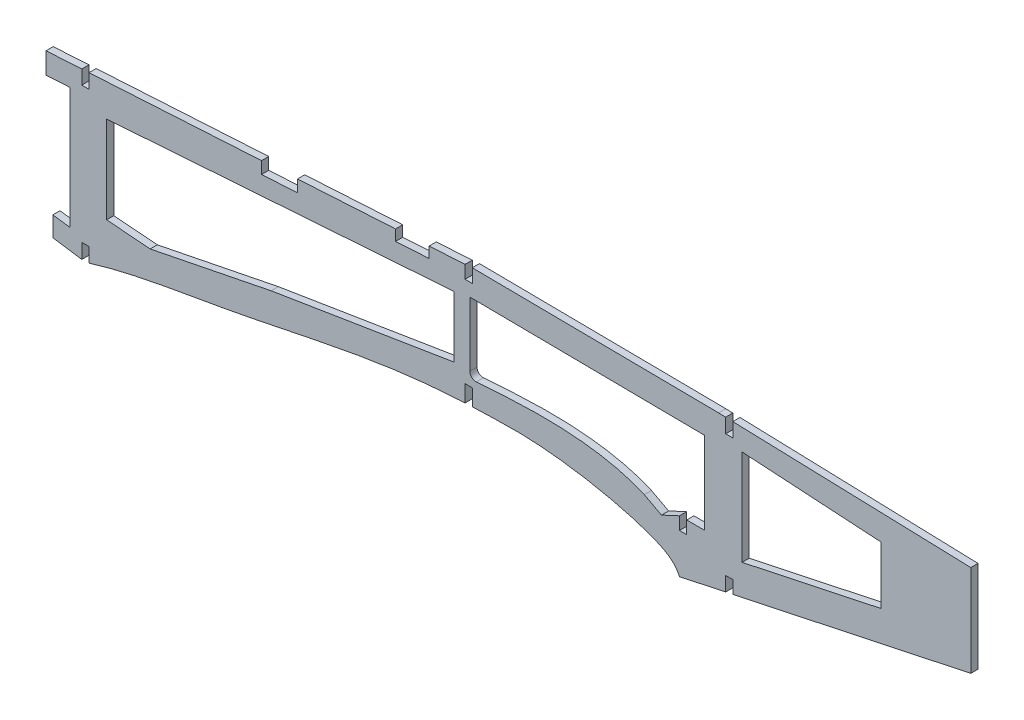
SolidWorks part; units mm, degrees
ref_plane "Front Plane" through (0, 0, 0) normal (0, 0, 1) x (1, 0, 0)
ref_plane "Top Plane" through (0, 0, 0) normal (0, 1, 0) x (1, 0, 0)
ref_plane "Right Plane" through (0, 0, 0) normal (1, 0, 0) x (0, 0, -1)
sketch "Sketch1" plane through (0, 0, 0) normal (0, 0, 1) x (1, 0, 0)
  line L0 (0, 0) -> (110, 0) construction
  line L1 (110, 0) -> (110, 21) construction
  line L2 (0, 0) -> (110, 21)
  line L3 (23.5, 17.3139) -> (20, 16.6457)
  line L4 (0, 0) -> (20, 0)
  line L5 (20, 0) -> (20, 67.15) construction
  line L6 (0, 0) -> (0, 67.15) construction
  line L7 (0, 67.15) -> (110, 67.15) construction
  line L8 (110, 61.55) -> (110, 67.15)
  line L9 (0, 67.15) -> (110, 61.55)
  line L10 (23.5, 53.9381) -> (81.5, 50.9854)
  line L11 (81.5, 50.9854) -> (81.5, 28.3866)
  line L12 (23.5, 53.9381) -> (23.5, 17.3139)
  line L13 (23.5, 17.3139) -> (81.5, 28.3866)
  line L14 (110, 21) -> (110, 61.55) construction
  line L15 (112, 61.4482) -> (112, 21.3818)
  line L16 (110, 61.55) -> (112, 61.4482)
  line L17 (110, 21) -> (112, 21.3818)
  line L18 (10.9, 67.15) -> (10.9, 0)
  line L19 (0, 67.15) -> (-82.3902, 71.3444)
  line L20 (0, 0) -> (-182.0672, -34.7583)
  line L21 (-86.7, -36.2944) -> (-86.7, -57.7944)
  line L22 (-93.05, 89.1409) -> (-93.05, -40.6456)
  line L23 (-70.5516, 60.184) -> (7.4462, 55.0566)
  line L24 (-89.4413, 54.3923) -> (-89.4413, 37.6042)
  line L25 (-65.3332, 22.0194) -> (-42.2468, 20.2821) construction
  line L26 (-42.2468, 20.2821) -> (-21.4079, 14.5616) construction
  line L27 (-21.4079, 14.5616) -> (-8.5368, 8.8411) construction
  line L28 (-8.5368, 8.8411) -> (-2.8162, 7.0023) construction
  line L29 (-2.8162, 7.0023) -> (0, 0) construction
  line L30 (-235.9653, 18.0968) -> (-234.0715, 53.1142)
  line L31 (-238.05, 59.4719) -> (-238.05, 21) construction
  line L32 (-921.7383, -124.7627) -> (144.2786, -161.9889) construction
  line L34 (-226.3459, 60.184) -> (-104.3294, 60.184)
  line L35 (-82.0567, 37.6042) -> (-82.7237, 57.9466)
  line L36 (-82.3902, 71.3444) -> (-103.6, 72.4242)
  line L37 (-103.6, 72.4242) -> (-103.6, 67.1242)
  line L38 (-103.6, 67.1242) -> (-117.6, 67.1242)
  line L39 (-117.6, 67.1242) -> (-117.6, 72.6011)
  line L40 (-117.6, 72.6011) -> (-158.5, 72.6011)
  line L41 (-158.5, 72.6011) -> (-158.5, 68.6011)
  line L42 (-158.5, 68.6011) -> (-173.5, 69.3647)
  line L43 (-173.5, 69.3647) -> (-173.5, 73.3311)
  line L44 (-173.5, 73.3311) -> (-250.6778, 73.3311)
  line L45 (-250.6778, 73.3311) -> (-251.1351, 64.35)
  line L46 (-251.1351, 64.35) -> (-249.1426, 59.4719)
  line L47 (-249.1426, 59.4719) -> (-253.0614, 11.9612)
  spline_without_curve S0
  spline S1 degree 3 poles (-62.7428, 33.1676) (-50.008, 31.9642) (-31.0962, 32.5015) (-14.1751, 24.9914) (-9.6822, 22.192) knots 0 0 0 0 0.709755 1 1 1 1
  spline S2 degree 3 poles (-9.6822, 22.192) (-6.8917, 20.9668) (-4.0654, 23.2801) (1.077, 24.0309) (6.7349, 23.1276) (13.0796, 25.9871) (10.9, 30.3114) knots 0 0 0 0 0.304362 0.391412 0.603771 1 1 1 1
  spline S3 degree 3 poles (-65.3332, 22.0194) (-77.4805, 22.6509) (-98.8967, 23.1079) (-139.7694, 19.7032) (-187.7649, 10.9991) (-227.3069, 7.5749) (-246.6861, 2.6333) knots 0 0 0 0 0.199692 0.351003 0.672194 1 1 1 1
  spline S4 degree 3 poles (-62.7428, 33.1676) (-67.9368, 33.6388) (-74.1452, 31.6619) (-82.8627, 34.4448) (-82.0567, 37.6042) knots 0 0 0 0 0.65977 1 1 1 1
  spline S5 degree 3 poles (-104.3294, 60.184) (-100.5301, 59.5513) (-93.8007, 61.9485) (-88.7866, 56.5953) (-89.4413, 54.3923) knots 0 0 0 0 0.661964 1 1 1 1
  spline S6 degree 3 poles (-104.3294, 33.547) (-100.6826, 33.3941) (-97.3824, 32.6768) (-91.1309, 33.381) (-89.6784, 34.473) (-89.4413, 37.6042) knots 0 0 0 0 0.555991 0.846219 1 1 1 1
  spline S7 degree 3 poles (-104.3294, 33.547) (-116.4931, 34.3961) (-139.9294, 30.8214) (-169.9623, 27.1478) (-193.8607, 26.9431) (-204.0402, 24.0023) (-211.1217, 23.2564) (-214.8026, 19.376) (-215.2918, 15.9456) (-214.9447, 14.6164) (-218.1891, 14.6988) (-221.7312, 14.9192) (-230.6867, 16.3937) (-236.4685, 15.9971) (-235.9653, 18.0968) knots 0 0 0 0 0.241116 0.431915 0.666521 0.747659 0.783153 0.799752 0.821748 0.858269 0.866885 0.907914 0.932706 1 1 1 1
  spline S8 degree 3 poles (-82.7237, 57.9466) (-82.8248, 63.2577) (-71.0235, 59.3637) (-70.5516, 60.184) knots 0 0 0 0 1 1 1 1
  spline S9 degree 2 poles (7.4462, 55.0566) (12.5645, 55.8042) (10.9, 50.909) knots 0 0 0 1 1 1
  spline S10 degree 3 poles (-234.0715, 53.1142) (-234.3359, 55.4474) (-232.0516, 60.1047) (-228.0459, 60.2249) (-226.3459, 60.184) knots 0 0 0 0 0.618254 1 1 1 1
  spline S11 degree 2 poles (-253.0614, 11.9612) (-252.6953, 7.068) (-247.464, 8.0018) knots 0 0 0 1 1 1
  spline S12 degree 3 poles (-246.6861, 2.6333) (-248.9283, 3.1544) (-247.5659, 6.6016) (-247.464, 8.0018) knots 0 0 0 0 1 1 1 1
  point P55 (-93.05, 46.4253)
  dimension "D1" = 110
  dimension "D2" = 21
  dimension "D3" = 12.6
  dimension "D4" = 20
  dimension "D5" = 67.15
  dimension "D6" = 5.6
  dimension "D7" = 110
  dimension "D8" = 12
  dimension "D9" = 3.5
  dimension "D10" = 58
  dimension "D11" = 2
  dimension "D12" = 12.6
  dimension "D13" = 97.6
  dimension "D14" = 6.35
  dimension "D15" = 14
  dimension "D16" = 145
  dimension "D17" = 15
  dimension "D18" = 40.9
  dimension "D19" = 10.55
  dimension "D20" = 5.3
  dimension "D21" = 4
sketch "Sketch2" plane through (0, 0, 0) normal (0, 0, 1) x (1, 0, 0)
  line L0 (0, 0) -> (110, 21) construction
  line L1 (0, 0) -> (110, 21)
  line L2 (112, 61.4482) -> (112, 21.3818) construction
  line L3 (112, 61.4482) -> (112, 21.3818)
  line L4 (-70.5516, 60.184) -> (7.4462, 55.0566) construction
  line L5 (110, 21) -> (112, 21.3818) construction
  line L6 (110, 21) -> (112, 21.3818)
  line L7 (110, 61.55) -> (112, 61.4482) construction
  line L8 (110, 61.55) -> (112, 61.4482)
  line L9 (0, 67.15) -> (110, 61.55) construction
  line L10 (0, 67.15) -> (110, 61.55)
  line L11 (0, 67.15) -> (-82.3902, 71.3444) construction
  line L12 (0, 67.15) -> (-82.3902, 71.3444)
  line L13 (-82.3902, 71.3444) -> (-103.6, 72.4242) construction
  line L14 (-82.3902, 71.3444) -> (-103.6, 72.4242)
  line L15 (-103.6, 72.4242) -> (-103.6, 67.3782)
  line L16 (-103.6, 67.3782) -> (-117.6, 67.3782)
  line L17 (-117.6, 67.3782) -> (-117.6, 72.6011)
  line L18 (-117.6, 72.6011) -> (-158.5, 72.6011)
  line L19 (-158.5, 72.6011) -> (-158.5, 69.3647)
  line L20 (-158.5, 69.3647) -> (-173.5, 69.3647)
  line L21 (-173.5, 69.3647) -> (-173.5, 73.3311)
  line L22 (-173.5, 73.3311) -> (-250.6778, 73.3311) construction
  line L23 (-173.5, 73.3311) -> (-250.6778, 73.3311)
  line L24 (-250.6778, 73.3311) -> (-253.0614, 11.9612)
  line L25 (-89.4413, 54.3923) -> (-89.4413, 37.6042) construction
  line L26 (-226.3459, 60.184) -> (-104.3294, 60.184) construction
  line L27 (-235.9653, 18.0968) -> (-234.0715, 53.1142) construction
  line L28 (-89.4413, 54.3923) -> (-89.4413, 37.6042)
  line L29 (-226.3459, 60.184) -> (-104.3294, 60.184)
  line L30 (-235.9653, 18.0968) -> (-234.0715, 53.1142)
  line L31 (-82.0567, 37.6042) -> (-82.7237, 57.9466) construction
  line L32 (-70.5516, 60.184) -> (7.4462, 55.0566)
  line L33 (-82.0567, 37.6042) -> (-82.7237, 57.9466)
  line L34 (10.9, 50.909) -> (10.9, 30.3114)
  line L35 (81.5, 50.9854) -> (81.5, 28.3866) construction
  line L36 (23.5, 17.3139) -> (81.5, 28.3866) construction
  line L37 (23.5, 53.9381) -> (81.5, 50.9854) construction
  line L38 (23.5, 53.9381) -> (23.5, 17.3139) construction
  line L39 (81.5, 48.1342) -> (81.5, 30.8681)
  line L40 (27.0626, 17.994) -> (79.0626, 27.9213)
  line L41 (26.6525, 53.7776) -> (78.6525, 51.1303)
  line L42 (23.5, 50.7815) -> (23.5, 20.9408)
  line L43 (-158.5, 72.6011) -> (-158.5, 68.6011) construction
  arc A0 (26.6525, 53.7776) -> (23.5, 50.7815) centre (26.5, 50.7815) ccw
  arc A1 (27.0626, 17.994) -> (23.5, 20.9408) centre (26.5, 20.9408) cw
  arc A2 (81.5, 30.8681) -> (79.0626, 27.9213) centre (78.5, 30.8681) cw
  arc A3 (81.5, 48.1342) -> (78.6525, 51.1303) centre (78.5, 48.1342) ccw
  parabola Q0 (-253.0614, 11.9612) -> (-247.464, 8.0018) focus (-250.6889, 9.8561) apex (-251.6748, 8.6753) construction
  parabola Q1 (-253.0614, 11.9612) -> (-247.464, 8.0018) focus (-250.6889, 9.8561) apex (-251.6748, 8.6753)
  parabola Q2 (7.4462, 55.0566) -> (10.9, 50.909) focus (10.2347, 53.865) apex (10.8693, 54.3929) construction
  parabola Q3 (7.4462, 55.0566) -> (10.9, 50.909) focus (10.2347, 53.865) apex (10.8693, 54.3929)
  spline S0 degree 3 poles (1215.9924, 1366.2087) (-1689.2719, -1445.9602) (1160.7038, 1491.2702) (-1612.7605, -1453.4516) knots -5.972872 -5.972872 -5.972872 -5.972872 7.300913 7.300913 7.300913 7.300913 only from (-246.6861, 2.6333) to (-247.464, 8.0018) construction
  spline S1 degree 3 poles (-246.6861, 2.6333) (-248.9283, 3.1544) (-247.5659, 6.6016) (-247.464, 8.0018) knots 0 0 0 0 1 1 1 1
  spline S2 degree 3 poles (175.3636, 1967.872) (391.9741, -245.9956) (130.7811, 42.2402) (-139.7694, 19.7032) (-325.1272, -13.9116) (-514.1452, 28.671) (-309.5796, -1983.4136) knots -3.777296 -3.777296 -3.777296 -3.777296 0.199692 0.351003 0.672194 3.290466 3.290466 3.290466 3.290466 only from (-65.3332, 22.0194) to (-246.6861, 2.6333) construction
  spline S3 degree 3 poles (-65.3332, 22.0194) (-77.4805, 22.6509) (-98.8967, 23.1079) (-139.7694, 19.7032) (-187.7649, 10.9991) (-227.3069, 7.5749) (-246.6861, 2.6333) knots 0 0 0 0 0.199692 0.351003 0.672194 1 1 1 1
  spline S4 degree 5 poles (1876.0426, 360.0904) (-1729.8867, -1179.746) (583.5253, 1803.2982) (78.4446, -2000.9415) (-313.5377, 2017.6127) (349.0217, -1969.1752) knots -2.469726 -2.469726 -2.469726 -2.469726 -2.469726 -2.469726 2.883008 2.883008 2.883008 2.883008 2.883008 2.883008 only from (-65.3332, 22.0194) to (0, 0) construction
  spline S5 degree 5 poles (-65.3332, 22.0194) (-42.2468, 20.2821) (-21.4079, 14.5616) (-8.5368, 8.8411) (-2.8162, 7.0023) (0, 0) knots 0 0 0 0 0 0 1 1 1 1 1 1
  spline S6 degree 3 poles (-2003.4226, -592.8129) (-74.6134, 83.2569) (-127.2178, 29.3158) (-83.3934, 34.2526) (-91.8628, 46.616) (-191.2637, 2034.7775) knots -4.772522 -4.772522 -4.772522 -4.772522 0.555991 0.846219 2.237697 2.237697 2.237697 2.237697 only from (-104.3294, 33.547) to (-89.4413, 37.6042) construction
  spline S7 degree 3 poles (-884.1428, -1800.4231) (147.9483, 84.9453) (-58.8059, 40.7444) (-169.9623, 27.1478) (-193.8607, 26.9431) (-204.0402, 24.0023) (-211.1217, 23.2564) (-214.8026, 19.376) (-215.2918, 15.9456) (-214.9447, 14.6164) (-218.1891, 14.6988) (-221.7312, 14.9192) (-259.045, 21.0628) (-280.7399, -17.3172) (1437.9042, 1112.0112) knots -1.800378 -1.800378 -1.800378 -1.800378 0.241116 0.431915 0.666521 0.747659 0.783153 0.799752 0.821748 0.858269 0.866885 0.907914 0.932706 1.421519 1.421519 1.421519 1.421519 only from (-104.3294, 33.547) to (-235.9653, 18.0968) construction
  spline S8 degree 3 poles (879.86, 1711.5652) (-207.6215, -132.0929) (-295.8251, 232.0271) (-122.4858, -93.2389) (-314.6686, 2056.7417) knots -5.484197 -5.484197 -5.484197 -5.484197 0.618254 6.842445 6.842445 6.842445 6.842445 only from (-234.0715, 53.1142) to (-226.3459, 60.184) construction
  spline S9 degree 3 poles (-104.3294, 33.547) (-100.6826, 33.3941) (-97.3824, 32.6768) (-91.1309, 33.381) (-89.6784, 34.473) (-89.4413, 37.6042) knots 0 0 0 0 0.555991 0.846219 1 1 1 1
  spline S10 degree 3 poles (-104.3294, 33.547) (-116.4931, 34.3961) (-139.9294, 30.8214) (-169.9623, 27.1478) (-193.8607, 26.9431) (-204.0402, 24.0023) (-211.1217, 23.2564) (-214.8026, 19.376) (-215.2918, 15.9456) (-214.9447, 14.6164) (-218.1891, 14.6988) (-221.7312, 14.9192) (-230.6867, 16.3937) (-236.4685, 15.9971) (-235.9653, 18.0968) knots 0 0 0 0 0.241116 0.431915 0.666521 0.747659 0.783153 0.799752 0.821748 0.858269 0.866885 0.907914 0.932706 1 1 1 1
  spline S11 degree 3 poles (-234.0715, 53.1142) (-234.3359, 55.4474) (-232.0516, 60.1047) (-228.0459, 60.2249) (-226.3459, 60.184) knots 0 0 0 0 0.618254 1 1 1 1
  spline S12 degree 3 poles (319.5224, 2014.3086) (-192.9155, -111.4852) (-73.7068, 193.2347) (-74.1309, -42.5933) (-2079.8517, 234.6153) knots -4.398535 -4.398535 -4.398535 -4.398535 0.661964 3.952777 3.952777 3.952777 3.952777 only from (-104.3294, 60.184) to (-89.4413, 54.3923) construction
  spline S13 degree 3 poles (-104.3294, 60.184) (-100.5301, 59.5513) (-93.8007, 61.9485) (-88.7866, 56.5953) (-89.4413, 54.3923) knots 0 0 0 0 0.661964 1 1 1 1
  spline S14 degree 3 poles (-476.921, 1966.6082) (-22.6367, -59.8265) (-22.4132, 20.601) (1.077, 24.0309) (25.1351, 20.1898) (79.5245, 97.6802) (-1928.1805, 515.6228) knots -2.154256 -2.154256 -2.154256 -2.154256 0.304362 0.391412 0.603771 3.262307 3.262307 3.262307 3.262307 only from (-9.6822, 22.192) to (10.9, 30.3114) construction
  spline S15 degree 3 poles (290.3742, 1996.6931) (-276.3479, -157.1226) (45.2421, 284.1781) (112.1059, -304.2564) (-1943.388, -409.2218) knots -4.781032 -4.781032 -4.781032 -4.781032 0.709755 6.530859 6.530859 6.530859 6.530859 only from (-62.7428, 33.1676) to (-9.6822, 22.192) construction
  spline S16 degree 3 poles (1014.7339, -1650.8552) (-65.1434, 157.9827) (-20.1321, -37.6544) (-136.3103, 72.496) (1711.8022, 920.8151) knots -4.712693 -4.712693 -4.712693 -4.712693 0.65977 3.302586 3.302586 3.302586 3.302586 only from (-62.7428, 33.1676) to (-82.0567, 37.6042) construction
  spline S17 degree 3 poles (1566.4817, -1072.7309) (-1852.9005, 1150.0589) (1734.6604, -974.3467) (-1819.0286, 1030.9337) knots -3.685572 -3.685572 -3.685572 -3.685572 4.790703 4.790703 4.790703 4.790703 only from (-82.7237, 57.9466) to (-70.5516, 60.184) construction
  spline S18 degree 3 poles (-9.6822, 22.192) (-6.8917, 20.9668) (-4.0654, 23.2801) (1.077, 24.0309) (6.7349, 23.1276) (13.0796, 25.9871) (10.9, 30.3114) knots 0 0 0 0 0.304362 0.391412 0.603771 1 1 1 1
  spline S19 degree 3 poles (-62.7428, 33.1676) (-50.008, 31.9642) (-31.0962, 32.5015) (-14.1751, 24.9914) (-9.6822, 22.192) knots 0 0 0 0 0.709755 1 1 1 1
  spline S20 degree 3 poles (-62.7428, 33.1676) (-67.9368, 33.6388) (-74.1452, 31.6619) (-82.8627, 34.4448) (-82.0567, 37.6042) knots 0 0 0 0 0.65977 1 1 1 1
  spline S21 degree 3 poles (-82.7237, 57.9466) (-82.8248, 63.2577) (-71.0235, 59.3637) (-70.5516, 60.184) knots 0 0 0 0 1 1 1 1
  point P6 (-2.1894, 23.46)
  dimension "D1" = 3
  dimension "D2" = 3
  dimension "D3" = 14
sketch "Sketch3" plane through (0, 0, 0) normal (0, 0, -1) x (-1, 0, 0)
  line L0 (-20, 0) -> (-20, 67.15) construction
  line L1 (-20, 0) -> (-20, 67.15)
  line L2 (0, 67.15) -> (-110, 61.55) construction
  line L3 (0, 23.8107) -> (0, -7.1001) construction
  line L4 (0, 67.15) -> (-110, 61.55)
  line L5 (-17, 66.2845) -> (-17, 60.5845)
  line L6 (-17, 60.5845) -> (-20, 60.5845)
  line L7 (-20, 60.5845) -> (-20, 66.1318)
  line L8 (-20, 66.1318) -> (-17, 66.2845)
  line L9 (0, 0) -> (-110, 21) construction
  line L10 (0, 0) -> (-110, 21)
  line L11 (-17, 8.7455) -> (-17, 3.2455)
  line L12 (-17, 8.7455) -> (-20, 8.7455)
  line L13 (-20, 8.7455) -> (-20, 3.7748)
  line L14 (-20, 3.7748) -> (-17, 3.2455)
  line L15 (88, 71.63) -> (88, 66.2827)
  line L16 (91, 71.7827) -> (91, 66.2827)
  line L17 (82.3902, 71.3444) -> (103.6, 72.4242) construction
  line L18 (91, 66.2827) -> (88, 66.2827)
  line L19 (88, 71.63) -> (91, 71.7827)
  line L24 (0, 23.8107) -> (0, 17.8107)
  line L25 (-3, 23.7752) -> (-3, 17.8107)
  line L26 (0, 17.8107) -> (-3, 17.8107)
  line L27 (-3, 23.7752) -> (0, 23.8107)
  line L28 (88, 160.3101) -> (88, -51.3247)
  line L30 (91, 29.1781) -> (91, 22.6781)
  line L31 (91, 29.1781) -> (88, 29.1781)
  line L32 (88, 29.1781) -> (88, 22.6781)
  line L33 (88, 22.6781) -> (91, 22.6781)
  spline S1 degree 3 poles (9.6822, 22.192) (6.8917, 20.9668) (4.0654, 23.2801) (-1.077, 24.0309) (-6.7349, 23.1276) (-13.0796, 25.9871) (-10.9, 30.3114) knots 0 0 0 0 0.304362 0.391412 0.603771 1 1 1 1 construction
  spline S2 degree 3 poles (65.3332, 22.0194) (77.4805, 22.6509) (98.8967, 23.1079) (139.7694, 19.7032) (187.7649, 10.9991) (227.3069, 7.5749) (246.6861, 2.6333) knots 0 0 0 0 0.199692 0.351003 0.672194 1 1 1 1 construction
  dimension "D1" = 3
  dimension "D2" = 5.7
  dimension "D3" = 5.5
  dimension "D4" = 6.5
  dimension "D5" = 3
  dimension "D6" = 5.5
  dimension "D7" = 108
  dimension "D8" = 20
  dimension "D9" = 6
  dimension "D10" = 3
sketch "Sketch4" plane through (0, 0, 0) normal (0, 0, -1) x (-1, 0, 0)
  line L0 (119.2548, -0.35) -> (-119.2548, -0.35)
  line L1 (0, -0.35) -> (0, 67.15)
  line L57 (253.3406, -1.2994) -> (254.1722, 60.1111)
  line L58 (254.1722, 60.1111) -> (174.8745, 64.2669)
  line L59 (174.8745, 64.2669) -> (174.8979, 65.3912)
  line L60 (174.8979, 65.3912) -> (159.85, 57.5564)
  line L61 (159.85, 57.5564) -> (159.9757, 68.9387)
  line L62 (159.9757, 68.9387) -> (119.0846, 69.7894)
  line L63 (119.0846, 69.7894) -> (118.9759, 64.5677)
  line L64 (118.9759, 64.5677) -> (104.979, 64.8589)
  line L65 (104.979, 64.8589) -> (105.0839, 69.9038)
  line L66 (105.0839, 69.9038) -> (89.4708, 69.4342)
  line L70 (89.4708, 69.4342) -> (-15.6177, 66.2738)
  line L74 (-15.6177, 66.2738) -> (-110.6977, 63.4144)
  line L75 (-110.6977, 63.4144) -> (-111.5311, 23.3567)
  line L76 (-111.5311, 23.3567) -> (0, -0.35)
  parabola Q2 (247.5437, -4.9604) -> (253.3406, -1.2994) focus (250.8611, -3.2775) apex (251.7839, -4.5082)
  spline S8 degree 3 poles (66.396, 18.2199) (74.9521, 18.2164) (83.5166, 18.0283) (92.0622, 17.5345) knots 0.875946 0.875946 0.875946 0.875946 1.016409 1.016409 1.016409 1.016409
  spline S9 degree 3 poles (92.0622, 17.5345) (95.666, 17.3341) (108.4649, 16.4288) (140.621, 12.1175) (188.1196, 1.0175) (227.4402, -4.3854) (246.5472, -10.2927) knots 0 0 0 0 0.059228 0.210539 0.53173 0.859537 0.859537 0.859537 0.859537
  spline S10 degree 3 poles (246.5472, -10.2927) (248.8088, -9.8636) (247.5883, -6.3636) (247.5437, -4.9604) knots 0 0 0 0 1 1 1 1
  spline S11 degree 5 poles (0, -0.35) (3.1789, 6.4953) (8.9878, 8.0322) (22.1406, 13.0712) (43.2504, 17.6932) (66.396, 18.2199) knots 0 0 0 0 0 0 1 1 1 1 1 1
  point P3 (0, -0.35)
  point P4 (0, -0.35)
  point P15 (0, 0)
  dimension "D1" = 12
  dimension "D2" = 67.5
sketch "Sketch6" plane through (0, 0, -3) normal (0, 0, -1) x (-1, 0, 0)
  line L0 (0, -81.2122) -> (0, 80.5122) construction
  line L1 (-10.5, 55.95) -> (87.47, 56.9492)
  line L2 (-10.5, 55.95) -> (-10.5, 21.65)
  line L3 (-3, 21.65) -> (-10.5, 21.65)
  line L4 (0, 21.65) -> (0, 16.35)
  line L5 (0, 16.35) -> (-3, 16.35)
  line L6 (-3, 21.65) -> (-3, 16.35)
  line L7 (0, 21.65) -> (7.5224, 18.1423)
  line L8 (7.5224, 18.1423) -> (14.7017, 21.9596)
  line L9 (87.47, 56.9492) -> (87.47, 30.1297)
  line L10 (87.47, 27.441) -> (87.47, 17.771) construction
  line L11 (78.3036, 17.771) -> (96.6364, 17.771) construction
  line L12 (0, -0.35) -> (-19.25, 3.7417)
  line L13 (104.45, 66.8886) -> (104.45, 62.3808)
  line L14 (-16.3334, 66.995) -> (86.45, 68.0433)
  line L15 (-26.1, 57.7585) -> (-26.1, 17.8747)
  line L16 (-111.5311, 23.3567) -> (0, -0.35) construction
  line L17 (-19.25, 66.904) -> (-19.25, 60.904)
  line L18 (-111.5311, 23.3567) -> (-22.25, 4.3794)
  line L19 (118.45, 66.0678) -> (118.45, 61.5601)
  line L21 (-19.25, 9.7417) -> (-19.25, 3.7417)
  line L25 (-19.25, 66.904) -> (-19.25, 60.904)
  line L26 (-19.25, 60.904) -> (-22.25, 60.904)
  line L27 (-22.25, 66.8105) -> (-22.25, 60.904)
  line L29 (86.45, 82.6833) -> (86.45, 9.104) construction
  line L30 (104.45, 62.3808) -> (118.45, 61.5601)
  line L32 (86.45, 68.0433) -> (86.45, 62.3703)
  line L33 (86.45, 62.3703) -> (89.45, 62.3703)
  line L34 (89.45, 67.768) -> (89.45, 62.3703)
  line L35 (86.45, 17.6703) -> (89.45, 17.6703)
  line L36 (86.45, 17.6703) -> (86.45, 24.6703)
  line L37 (86.45, 24.6703) -> (89.45, 24.6703)
  line L38 (89.45, 17.6703) -> (89.45, 24.6703)
  line L39 (159.35, 63.6699) -> (159.35, 58.6614)
  line L40 (174.35, 62.7905) -> (174.35, 57.7819)
  line L41 (159.35, 58.6614) -> (174.35, 57.7819)
  line L42 (-16.3334, 66.995) -> (-19.25, 66.904)
  line L43 (93.97, 55.6703) -> (93.97, 30.1703)
  line L44 (238.97, 45.4839) -> (238.97, 9.104)
  line L45 (254.27, -1.2771) -> (254.27, 49.29)
  line L46 (238.97, 45.4839) -> (93.97, 55.6703)
  line L47 (238.97, 9.104) -> (220.8231, 7.6436)
  line L48 (220.8231, 7.6436) -> (170.3292, 17.771)
  line L49 (170.3292, 17.771) -> (93.97, 30.1703)
  line L50 (-26.1, 17.8747) -> (-84.1, 30.203)
  line L51 (-84.1, 30.203) -> (-84.1, 54.203)
  line L52 (-26.1, 57.7585) -> (-84.1, 54.203)
  line L53 (118.45, 66.0678) -> (159.35, 63.6699)
  line L54 (174.35, 62.7905) -> (246.35, 58.5694)
  line L55 (-19.25, 9.7417) -> (-19.25, 3.7417)
  line L56 (-19.25, 9.7417) -> (-22.25, 9.7417)
  line L57 (-22.25, 9.7417) -> (-22.25, 4.3794)
  line L58 (-22.25, 66.8105) -> (-111.5311, 64.0267)
  line L59 (254.27, 58.1051) -> (264.27, 57.5188)
  line L60 (89.45, 67.768) -> (254.27, 58.1051) construction
  line L61 (89.45, 67.768) -> (104.45, 66.8886)
  line L62 (246.35, 52.5694) -> (246.35, -10.2318) construction
  line L63 (246.35, -10.2318) -> (246.35, -4.2318)
  line L64 (264.27, 48.7037) -> (254.27, 49.29)
  line L66 (246.35, 58.5694) -> (246.35, 52.5694)
  line L67 (261.435, -0.35) -> (261.435, -8.6139)
  line L69 (254.27, -1.2771) -> (261.435, -0.35)
  line L70 (264.27, 57.5188) -> (264.27, 48.7037)
  line L71 (249.35, 58.3935) -> (249.35, 52.5694)
  line L72 (246.35, 52.5694) -> (249.35, 52.5694)
  line L73 (249.35, 58.3935) -> (254.27, 58.1051)
  line L74 (249.35, -4.2318) -> (249.35, -10.4223)
  line L75 (246.35, -4.2318) -> (249.35, -4.2318)
  line L76 (249.35, -10.4223) -> (261.435, -8.6139)
  line L77 (246.35, -10.2318) -> (246.35, -23.1088) construction
  line L78 (-111.5311, 64.0267) -> (-121.5262, 63.715)
  line L79 (-111.5311, 23.3567) -> (-121.5262, 25.4812)
  line L80 (-121.5262, 63.715) -> (-121.5262, 25.4812)
  arc A1 (84.7894, 27.6362) -> (87.47, 30.1297) centre (84.97, 30.1297) ccw
  spline S0 degree 3 poles (-77.6637, 1965.2461) (-403.1026, -225.9067) (-128.1526, 48.1531) (140.621, 12.1175) (324.0581, -30.7502) (514.9719, 2.2988) (209.7722, -1996.9316) knots -3.912695 -3.912695 -3.912695 -3.912695 0.059228 0.210539 0.53173 3.149975 3.149975 3.149975 3.149975 only from (92.0622, 17.5345) to (246.5472, -10.2927) construction
  spline S1 degree 3 poles (7.5224, 18.1423) (15.8431, 23.4586) (31.7661, 27.749) (54.2955, 29.2195) (70.8321, 28.623) (81.0266, 27.9088) (84.7894, 27.6362) knots 0 0 0 0 0.360279 0.59219 0.828481 0.967074 0.967074 0.967074 0.967074
  spline S2 degree 3 poles (-72.1435, 1973.9319) (-667.3868, -1967.4883) (657.6539, 2002.3942) (321.1173, -1939.6078) knots -2.901307 -2.901307 -2.901307 -2.901307 4.225484 4.225484 4.225484 4.225484 only from (66.396, 18.2199) to (92.0622, 17.5345) construction
  spline S3 degree 5 poles (-451.6238, -1948.659) (418.7135, 1998.167) (-183.0533, -1994.4986) (-488.3696, 1831.0433) (1665.7875, -1269.0189) (-1854.6198, 457.4284) knots -1.883035 -1.883035 -1.883035 -1.883035 -1.883035 -1.883035 3.469724 3.469724 3.469724 3.469724 3.469724 3.469724 only from (0, -0.35) to (66.396, 18.2199) construction
  spline S4 degree 5 poles (0, -0.35) (3.1789, 6.4953) (8.9878, 8.0322) (22.1406, 13.0712) (43.2504, 17.6932) (66.396, 18.2199) knots 0 0 0 0 0 0 1 1 1 1 1 1
  spline S5 degree 3 poles (66.396, 18.2199) (74.9521, 18.2164) (83.5166, 18.0283) (92.0622, 17.5345) knots 0.875946 0.875946 0.875946 0.875946 1.016409 1.016409 1.016409 1.016409
  spline S6 degree 3 poles (92.0622, 17.5345) (95.666, 17.3341) (108.4649, 16.4288) (140.621, 12.1175) (188.0527, 1.0331) (227.3036, -4.3666) (246.35, -10.2318) knots 0 0 0 0 0.059228 0.210539 0.53173 0.858409 0.858409 0.858409 0.858409
  spline S9 degree 3 poles (65.3332, 22.0194) (77.4805, 22.6509) (98.8967, 23.1079) (139.7694, 19.7032) (187.7649, 10.9991) (227.3069, 7.5749) (246.6861, 2.6333) knots 0 0 0 0 0.199692 0.351003 0.672194 1 1 1 1 construction
  point P4 (0, -0.35)
  point P27 (87.47, 17.771)
  point P68 (238.97, 27.294)
  point P72 (254.27, 28.414)
  dimension "D5" = 34.3
  dimension "D12" = 5
  dimension "D1" = 22
  dimension "D2" = 3
  dimension "D3" = 5.3
  dimension "D4" = 10.5
  dimension "D6" = 25
  dimension "D7" = 8.3
  dimension "D8" = 28
  dimension "D9" = 97.97
  dimension "D10" = 18
  dimension "D11" = 9.67
  dimension "D13" = 87.47
  dimension "D14" = 8.75
  dimension "D15" = 3
  dimension "D16" = 6
  dimension "D17" = 1.7002
  dimension "D18" = 3
  dimension "D19" = 4.5
  dimension "D20" = 7
  dimension "D21" = 37.7
  dimension "D22" = 105.7
  dimension "D23" = 3
  dimension "D24" = 3
  dimension "D25" = 14
  dimension "D26" = 5
  dimension "D27" = 6
  dimension "D28" = 40.9
  dimension "D29" = 15
  dimension "D30" = 8.8
  dimension "D31" = 40.67
  dimension "D32" = 6.5
  dimension "D33" = 145
  dimension "D34" = 15.3
  dimension "D35" = 10
  dimension "D36" = 10
  dimension "D37" = 25.5
  dimension "D38" = 15.6
  dimension "D39" = 12.4
  dimension "D40" = 58
  dimension "D41" = 24
  dimension "D42" = 3.0126
  dimension "D43" = 72
  dimension "D44" = 6
  dimension "D45" = 3
  dimension "D46" = 3
extrude "Boss-Extrude2" add sketch "Sketch6" along normal blind 3
